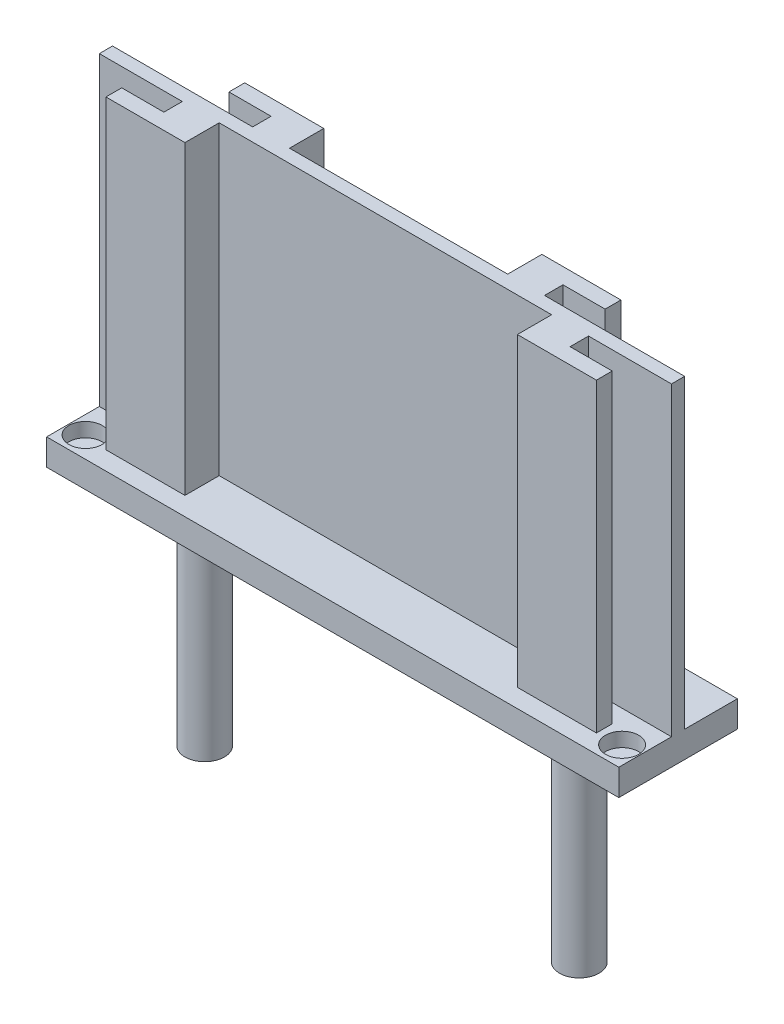
SolidWorks part; units mm, degrees
ref_plane "Front Plane" through (0, 0, 0) normal (0, 0, 1) x (1, 0, 0)
ref_plane "Top Plane" through (0, 0, 0) normal (0, 1, 0) x (1, 0, 0)
ref_plane "Right Plane" through (0, 0, 0) normal (1, 0, 0) x (0, 0, -1)
sketch "Sketch1" plane through (0, 0, 0) normal (0, 1, 0) x (1, 0, 0)
  line L1 (-54.3, -11.25) -> (54.3, -11.25)
  line L2 (-54.3, -11.25) -> (-54.3, 11.25)
  line L3 (-54.3, 11.25) -> (54.3, 11.25)
  line L4 (54.3, -11.25) -> (54.3, 11.25)
  line L5 (-54.3, -11.25) -> (54.3, 11.25) construction
  line L6 (-54.3, 11.25) -> (54.3, -11.25) construction
  point P0 (0, 0)
  dimension "D1" = 108.6
  dimension "D2" = 22.5
extrude "Boss-Extrude1" add sketch "Sketch1" along normal blind 5
sketch "Sketch2" plane through (0, 5, 0) normal (0, 1, 0) x (1, 0, 0)
  line L0 (-54.3, -11.25) -> (54.3, -11.25) construction
  line L2 (54.3, 11.25) -> (-54.3, 11.25) construction
  line L3 (0, 11.25) -> (0, -11.25) construction
  circle A4 centre (50.925, -7.25) radius 3.15 construction
  circle A5 centre (40.075, 7.25) radius 3.15 construction
  circle A6 centre (-50.925, -7.25) radius 3.15 construction
  circle A7 centre (-40.075, 7.25) radius 3.15 construction
  circle A8 centre (50.925, -7.25) radius 3.15
  circle A9 centre (40.075, 7.25) radius 3.15
  circle A10 centre (-50.925, -7.25) radius 3.15
  circle A11 centre (-40.075, 7.25) radius 3.15
extrude "Cut-Extrude1" cut sketch "Sketch2" against normal blind 2.7
sketch "Sketch3" plane through (0, 5, 0) normal (0, 1, 0) x (1, 0, 0)
  line L0 (-54.3, 0) -> (54.3, 0) construction
  line L1 (-54.3, 11.25) -> (-54.3, -11.25) construction
  line L2 (54.3, -11.25) -> (54.3, 11.25) construction
  line L3 (-38.55, -1.25) -> (-38.55, -4.75)
  line L4 (-54.3, 1.25) -> (54.3, 1.25)
  line L5 (-54.3, 1.25) -> (-54.3, -1.25)
  line L6 (-54.3, -1.25) -> (54.3, -1.25)
  line L7 (54.3, 1.25) -> (54.3, -1.25)
  line L8 (-38.55, -4.75) -> (-46.55, -4.75)
  line L9 (-46.55, -4.75) -> (-46.55, -7.75)
  line L14 (-46.55, -7.75) -> (-31.55, -7.75)
  line L15 (-31.55, -7.75) -> (-31.55, -1.25)
  line L16 (-38.55, -1.25) -> (-31.55, -1.25)
  line L17 (-27.7, 1.25) -> (-27.7, 4.75)
  line L18 (-27.7, 4.75) -> (-35.7, 4.75)
  line L19 (-35.7, 4.75) -> (-35.7, 7.75)
  line L24 (-35.7, 7.75) -> (-20.7, 7.75)
  line L25 (-20.7, 7.75) -> (-20.7, 1.25)
  line L26 (-27.7, 1.25) -> (-20.7, 1.25)
  point P10 (-54.3, 0)
  dimension "D1" = 2.5
  dimension "D2" = 3
  dimension "D3" = 8
  dimension "D4" = 7.75
  dimension "D5" = 3.5
  dimension "D7" = 22.75
  dimension "D10" = 3.5
  dimension "D11" = 3
  dimension "D12" = 18.6
  dimension "D13" = 33.6
  dimension "D16" = 8
extrude "Boss-Extrude2" add sketch "Sketch3" along normal blind 58
ref_plane "Plane1" through (0, 0, 0) normal (1, 0, 0) x (0, 0, -1)
mirror "Mirror1" about plane through (0, 0, 0) normal (1, 0, 0) of "Boss-Extrude2"
sketch "Sketch4" plane through (0, 0, 0) normal (0, -1, 0) x (1, 0, 0)
  line L0 (-54.3, -11.25) -> (-54.3, 11.25) construction
  line L2 (54.3, 11.25) -> (54.3, -11.25) construction
  circle A0 centre (-35.55, 0) radius 1.5
  circle A1 centre (35.55, 0) radius 1.5
  circle A2 centre (-35.55, 0) radius 3.75
  circle A3 centre (35.55, 0) radius 3.75
  dimension "D3" = 3
  dimension "D4" = 3
  dimension "D5" = 7.5
  dimension "D6" = 7.5
  dimension "D1" = 18.75
  dimension "D2" = 18.75
extrude "Boss-Extrude3" add sketch "Sketch4" along normal blind 42
fillet "Fillet1" radius 1 2 edges at (35.55, 0, -3.75) (-35.55, 0, -3.75)
